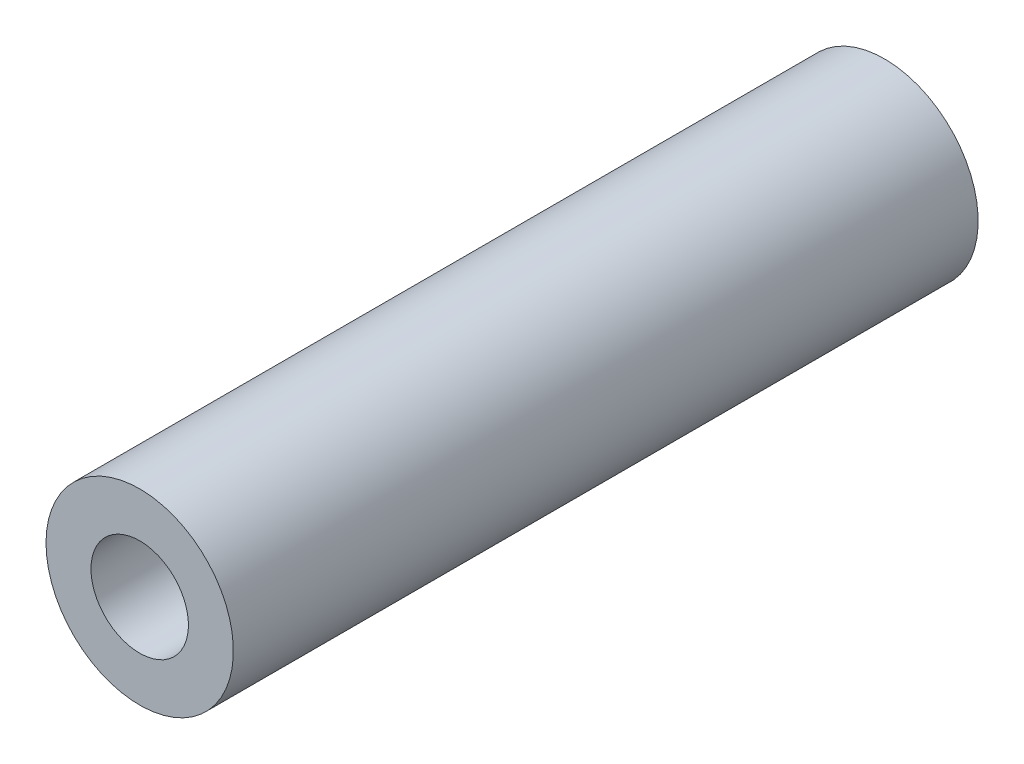
SolidWorks part; units mm, degrees
ref_plane "前视基准面" through (0, 0, 0) normal (0, 0, 1) x (1, 0, 0)
ref_plane "上视基准面" through (0, 0, 0) normal (0, 1, 0) x (1, 0, 0)
ref_plane "右视基准面" through (0, 0, 0) normal (1, 0, 0) x (0, 0, -1)
sketch "草图1" plane through (0, 0, 0) normal (0, 0, 1) x (1, 0, 0)
  circle A0 centre (0, 0) radius 2.6
  circle A1 centre (0, 0) radius 5
  dimension "D1" = 5.2
  dimension "D2" = 10
extrude "凸台-拉伸1" add sketch "草图1" along normal blind 39.75
